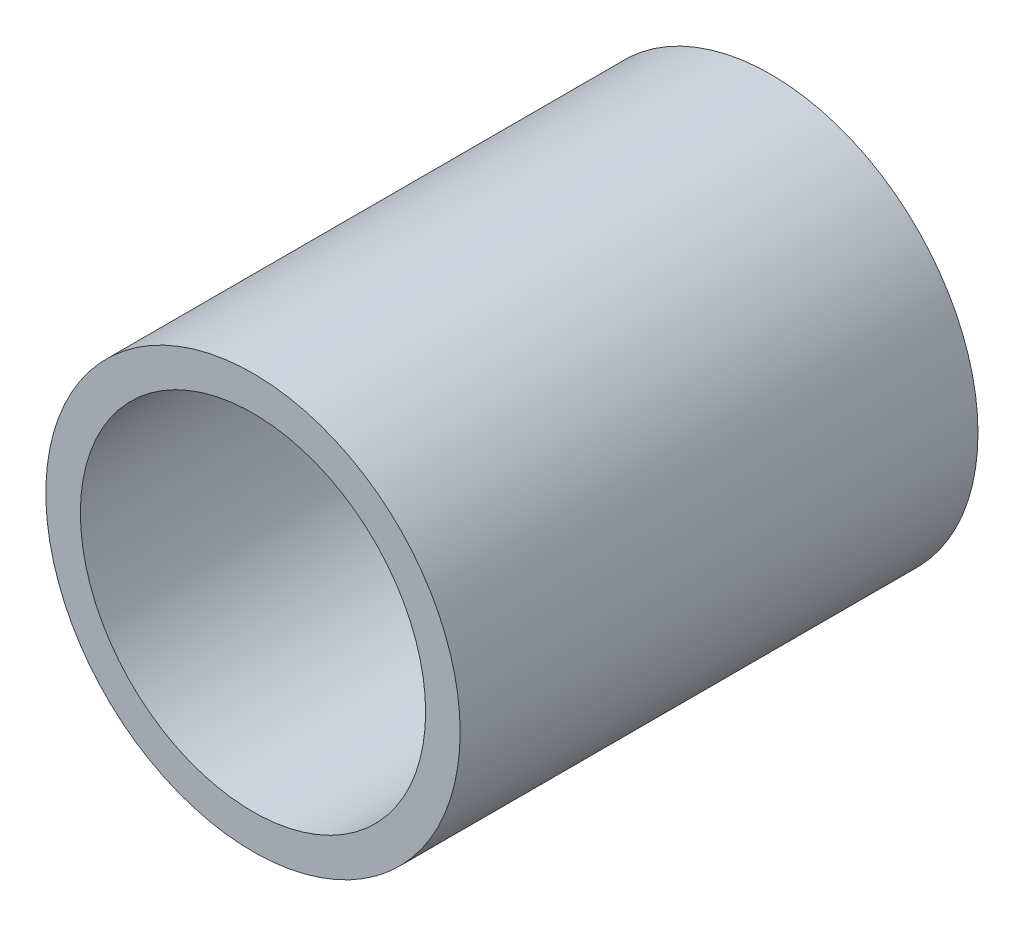
SolidWorks part; units mm, degrees
ref_plane "정면" through (0, 0, 0) normal (0, 0, 1) x (1, 0, 0)
ref_plane "윗면" through (0, 0, 0) normal (0, 1, 0) x (1, 0, 0)
ref_plane "우측면" through (0, 0, 0) normal (1, 0, 0) x (0, 0, -1)
sketch "스케치1" plane through (0, 0, 0) normal (0, 0, 1) x (1, 0, 0)
  circle A0 centre (0, 0) radius 6
  circle A1 centre (0, 0) radius 5
  dimension "D1" = 12
  dimension "D2" = 10
extrude "보스-돌출1" add sketch "스케치1" along normal blind 15
